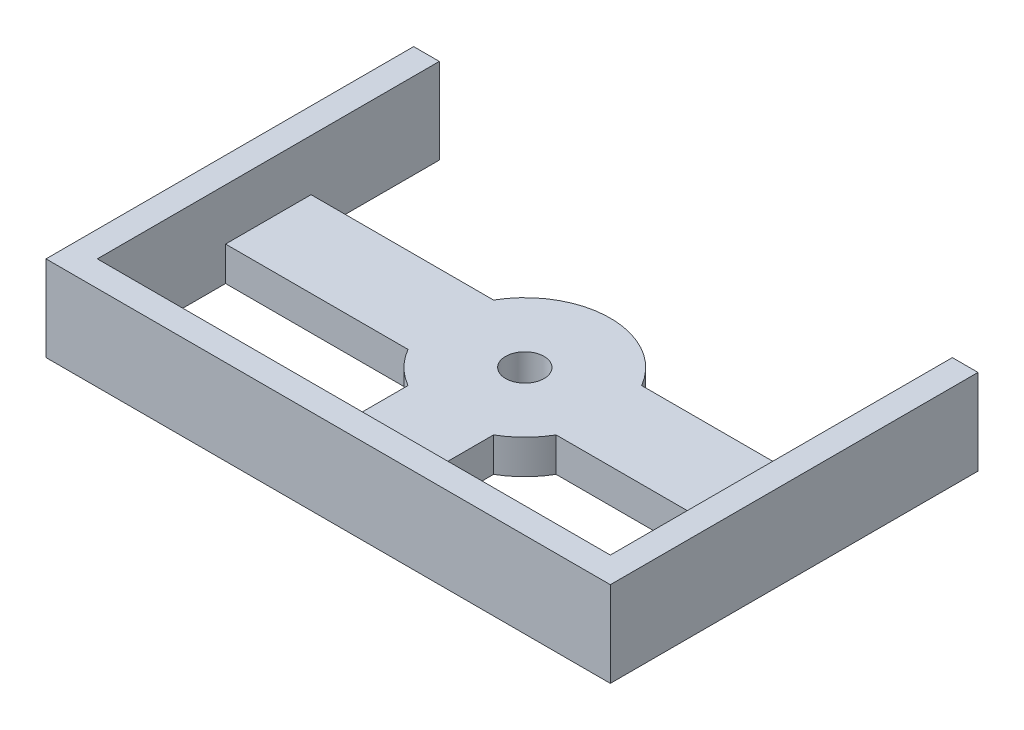
SolidWorks part; units mm, degrees
ref_plane "Front Plane" through (0, 0, 0) normal (0, 0, 1) x (1, 0, 0)
ref_plane "Top Plane" through (0, 0, 0) normal (0, 1, 0) x (1, 0, 0)
ref_plane "Right Plane" through (0, 0, 0) normal (1, 0, 0) x (0, 0, -1)
sketch "Sketch1" plane through (0, 0, 0) normal (0, 1, 0) x (1, 0, 0)
  line L1 (0, 0) -> (60, 0)
  line L2 (0, 0) -> (0, -40)
  line L3 (0, -40) -> (60, -40)
  line L4 (60, 0) -> (60, -40)
  line L5 (-3, 0) -> (63, 0)
  line L6 (-3, 0) -> (-3, -43)
  line L7 (-3, -43) -> (63, -43)
  line L8 (63, 0) -> (63, -43)
  dimension "D1" = 40
  dimension "D2" = 60
  dimension "D3" = 3
  dimension "D4" = 3
  dimension "D5" = 3
extrude "Boss-Extrude1" add sketch "Sketch1" along normal blind 10 contours L8 L5 L4 L3 L2 L6 L7
sketch "Sketch2" plane through (0, 0, 0) normal (0, 1, 0) x (1, 0, 0)
  line L0 (0, -25) -> (21.3397, -25)
  line L1 (0, -40) -> (60, -40)
  line L2 (0, -40) -> (0, 0)
  line L3 (0, 0) -> (60, 0)
  line L4 (60, -40) -> (60, 0)
  line L5 (0, -15) -> (21.3397, -15)
  line L6 (25, -40) -> (25, -28.6603)
  line L7 (30, -20) -> (30, -39.9752) construction
  line L8 (35, -40) -> (35, -28.6603)
  line L9 (60, -25) -> (38.6603, -25)
  line L10 (60, -15) -> (38.6603, -15)
  circle A0 centre (30, -20) radius 2.25
  arc A1 (21.3397, -25) -> (25, -28.6603) centre (30, -20) ccw
  arc A2 (21.3397, -15) -> (21.3397, -25) centre (30, -20) ccw construction
  arc A3 (25, -28.6603) -> (30, -30) centre (30, -20) ccw construction
  arc A4 (30, -30) -> (38.6603, -25) centre (30, -20) ccw
  arc A5 (38.6603, -25) -> (38.6603, -15) centre (30, -20) ccw construction
  arc A6 (38.6603, -15) -> (21.3397, -15) centre (30, -20) ccw
  point P22 (35.836, -28.1204)
  dimension "D2" = 4.5
  dimension "D4" = 20
  dimension "D1" = 30
  dimension "D3" = 20
  dimension "D5" = 5
  dimension "D6" = 5
  dimension "D7" = 5
extrude "Boss-Extrude2" add sketch "Sketch2" along normal blind 4
